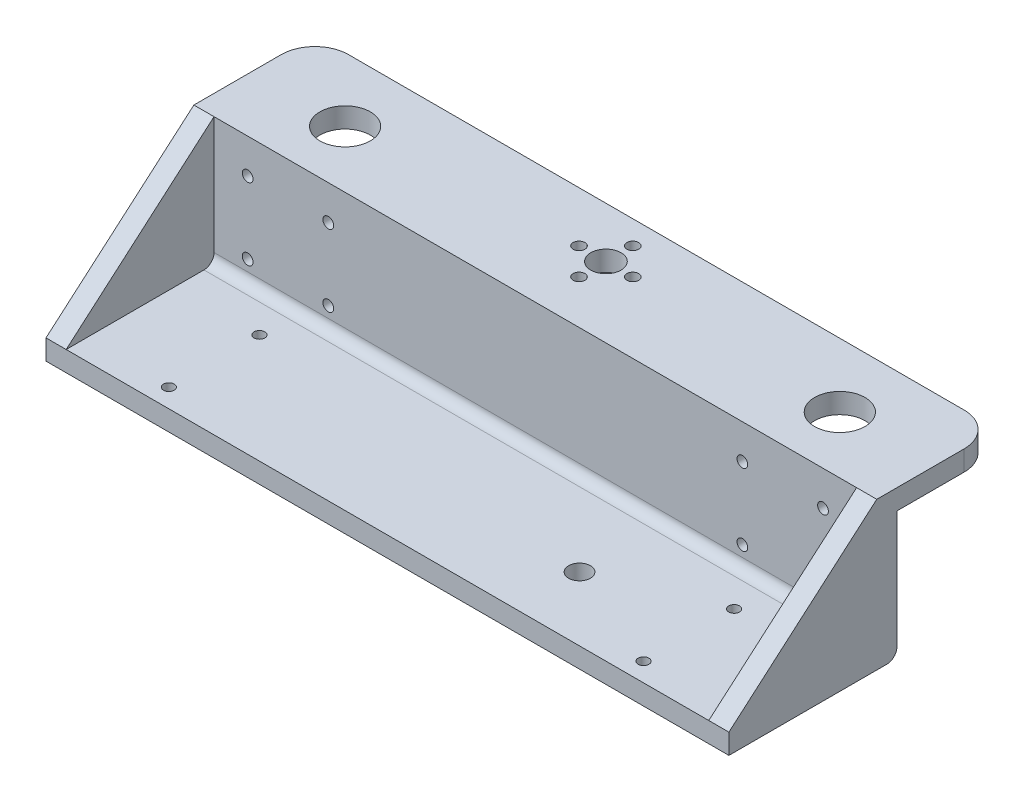
SolidWorks part; units mm, degrees
ref_plane "Plan de face" through (0, 0, 0) normal (0, 0, 1) x (1, 0, 0)
ref_plane "Plan de dessus" through (0, 0, 0) normal (0, 1, 0) x (1, 0, 0)
ref_plane "Plan de droite" through (0, 0, 0) normal (1, 0, 0) x (0, 0, -1)
sketch "Esquisse1" plane through (0, 0, 0) normal (0, 0, 1) x (1, 0, 0)
  line L1 (-101.6, -16) -> (101.6, -16)
  line L2 (-101.6, -16) -> (-101.6, 16)
  line L3 (-101.6, 16) -> (101.6, 16)
  line L4 (101.6, -16) -> (101.6, 16)
  line L5 (-101.6, -16) -> (101.6, 16) construction
  line L6 (-101.6, 16) -> (101.6, -16) construction
  point P0 (0, 0)
  dimension "D1" = 203.2
  dimension "D2" = 32
extrude "Boss.-Extru.1" add sketch "Esquisse1" along normal blind 6
sketch "Esquisse2" plane through (0, 16, 0) normal (0, 1, 0) x (1, 0, 0)
  line L0 (-101.6, -6) -> (-101.6, 0) construction
  line L1 (101.6, -6) -> (-101.6, -6)
  line L2 (101.6, -6) -> (101.6, 30)
  line L3 (101.6, 30) -> (-101.6, 30)
  line L4 (-101.6, -6) -> (-101.6, 30)
  point P7 (-101.6, -3)
  dimension "D1" = 36
extrude "Boss.-Extru.2" add sketch "Esquisse2" along normal blind 6
sketch "Esquisse3" plane through (0, 22, 0) normal (0, 1, 0) x (1, 0, 0)
  line L0 (-73.6, 11) -> (73.6, 11) construction
  line L1 (101.6, 30) -> (-101.6, 30) construction
  line L3 (-101.6, -6) -> (101.6, -6) construction
  line L4 (0, 15) -> (0, 23) construction
  circle A0 centre (-73.6, 11) radius 7.5
  circle A1 centre (73.6, 11) radius 7.5
  circle A2 centre (0, 15) radius 4.5
  circle A3 centre (0, 15) radius 8 construction
  circle A4 centre (0, 23) radius 1.75
  circle A5 centre (0, 7) radius 1.75
  circle A6 centre (8, 15) radius 1.75
  circle A7 centre (-8, 15) radius 1.75
  point P6 (0, 30)
  point P7 (0, 11)
  dimension "D1" = 15
  dimension "D4" = 9
  dimension "D5" = 16
  dimension "D6" = 3.5
  dimension "D2" = 147.2
  dimension "D3" = 17
  dimension "D7" = 4
extrude "Enlèv. mat.-Extru.1" cut sketch "Esquisse3" against normal through all
sketch "Esquisse6" plane through (0, -16, 0) normal (0, -1, 0) x (1, 0, 0)
  line L1 (101.6, 0) -> (-101.6, 0)
  line L2 (101.6, 0) -> (101.6, 50)
  line L3 (101.6, 50) -> (-101.6, 50)
  line L4 (-101.6, 0) -> (-101.6, 50)
  dimension "D1" = 50
extrude "Boss.-Extru.4" add sketch "Esquisse6" along normal blind 6
sketch "Esquisse7" plane through (101.6, 0, 0) normal (1, 0, 0) x (0, 0, -1)
  line L0 (-50, -16) -> (-6, 22)
  line L1 (-6, 22) -> (0, 22)
  line L2 (-6, 22) -> (30, 22) construction
  line L3 (0, 22) -> (0, -16)
  line L4 (0, -22) -> (0, 16) construction
  line L5 (0, -16) -> (-50, -16)
  line L6 (-6, -16) -> (-6, 22) construction
extrude "Boss.-Extru.5" add sketch "Esquisse7" against normal blind 6
mirror "Symétrie1" about plane through (0, 0, 0) normal (1, 0, 0) of "Boss.-Extru.5"
fillet "Congé3" radius 3 2 edges at (0, -16, 6) (0, -22, 0)
fillet "Congé4" radius 10 2 edges at (101.6, 19, -30) (-101.6, 19, -30)
sketch "Esquisse8" plane through (0, 0, 0) normal (0, 0, -1) x (-1, 0, 0)
  line L0 (-101.6, -19) -> (-101.6, 16) construction
  line L2 (0, 0) -> (0, -19) construction
  line L3 (-101.6, -19) -> (101.6, -19) construction
  line L4 (-91.6, 16) -> (91.6, 16) construction
  point P0 (-85.6, 11.7)
  point P1 (-61.6, 11.7)
  point P2 (-85.6, -9.7)
  point P3 (-61.6, -9.7)
  point P4 (61.6, -9.7)
  point P5 (85.6, -9.7)
  point P6 (61.6, 11.7)
  point P7 (85.6, 11.7)
  dimension "D1" = 21.4
  dimension "D2" = 24
  dimension "D3" = 16
  dimension "D4" = 4.3
hole_wizard "Dégagement M31" positions "Esquisse3D1" profile "Esquisse10" hole size "M3" standard "Ansi Metric"
sketch3d "Esquisse3D1"
  point P0 (85.6, 11.7, 0)
  point P3 (61.6, 11.7, 0)
  point P6 (85.6, -9.7, 0)
  point P9 (61.6, -9.7, 0)
  point P12 (-61.6, 11.7, 0)
  point P15 (-85.6, 11.7, 0)
  point P18 (-61.6, -9.7, 0)
  point P21 (-85.6, -9.7, 0)
sketch "Esquisse10" plane through (85.6, 11.7, 0) normal (1, 0, 0) x (0, 1, 0)
  line L0 (0, 0) -> (0, 6.9614)
  line L1 (0, 6.9614) -> (1.6, 6)
  line L2 (1.6, 6) -> (1.6, 0)
  line L5 (1.6, 0) -> (0, 0)
  line L10 (0, 6.9614) -> (-1.6, 6) construction
  line L11 (0, -6.35) -> (0, 107.95) construction
  dimension "Diamètre du perçage" = 3.2
  dimension "Profondeur du perçage" = 6
  dimension "Angle de pointe" = 118
sketch "Esquisse11" plane through (0, -22, 0) normal (0, -1, 0) x (1, 0, 0)
  line L0 (101.6, 3) -> (101.6, 50) construction
  line L1 (101.6, 50) -> (-101.6, 50) construction
  circle A0 centre (38.1, 30.95) radius 3.2385
  dimension "D3" = 6.477
  dimension "D1" = 63.5
  dimension "D2" = 19.05
extrude "Enlèv. mat.-Extru.3" cut sketch "Esquisse11" against normal blind 6
sketch "Esquisse12" plane through (0, -16, 0) normal (0, 1, 0) x (1, 0, 0)
  line L0 (-70.62, -17.48) -> (70.62, -17.48) construction
  line L1 (-70.62, -44.42) -> (70.62, -44.42) construction
  line L2 (95.6, -50) -> (-95.6, -50) construction
  circle A0 centre (38.1, -30.95) radius 3.2385 construction
  point P0 (-70.62, -44.42)
  point P1 (-70.62, -17.48)
  point P2 (70.62, -44.42)
  point P3 (70.62, -17.48)
  point P8 (0, 0)
  point P9 (0, 0)
  dimension "D3" = 108.72
  dimension "D1" = 26.94
  dimension "D2" = 5.58
  dimension "D4" = 141.24
hole_wizard "Dégagement M32" positions "Esquisse3D2" profile "Esquisse13" hole size "M3" standard "Ansi Metric"
sketch3d "Esquisse3D2"
  point P0 (-70.62, -16, 17.48)
  point P3 (-70.62, -16, 44.42)
  point P6 (70.62, -16, 17.48)
  point P9 (70.62, -16, 44.42)
sketch "Esquisse13" plane through (-70.62, -16, 17.48) normal (1, 0, 0) x (0, 0, 1)
  line L0 (0, 0) -> (0, 6.9614)
  line L1 (0, 6.9614) -> (1.6, 6)
  line L2 (1.6, 6) -> (1.6, 0)
  line L5 (1.6, 0) -> (0, 0)
  line L10 (0, 6.9614) -> (-1.6, 6) construction
  line L11 (0, -6.35) -> (0, 107.95) construction
  dimension "Diamètre du perçage" = 3.2
  dimension "Profondeur du perçage" = 6
  dimension "Angle de pointe" = 118
